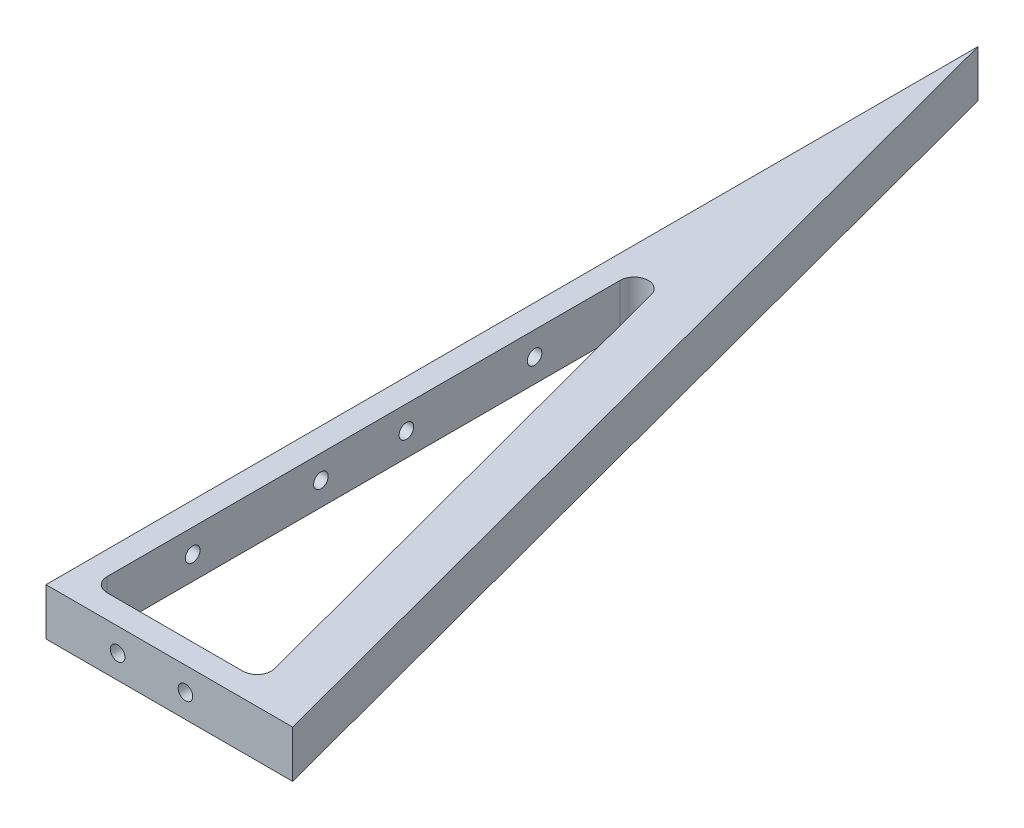
SolidWorks part; units mm, degrees
ref_plane "Front Plane" through (0, 0, 0) normal (0, 0, 1) x (1, 0, 0)
ref_plane "Top Plane" through (0, 0, 0) normal (0, 1, 0) x (1, 0, 0)
ref_plane "Right Plane" through (0, 0, 0) normal (1, 0, 0) x (0, 0, -1)
sketch "Sketch1" plane through (0, 0, 0) normal (0, 1, 0) x (1, 0, 0)
  line L0 (0, 0) -> (0, 198)
  line L1 (0, 198) -> (52.4, 0)
  line L2 (52.4, 0) -> (0, 0)
  line L3 (5, 8) -> (5, 116.9578)
  line L4 (10.9002, 117.7253) -> (39.7354, 8.7675)
  line L5 (36.8353, 5) -> (8, 5)
  arc A0 (5, 116.9578) -> (10.9002, 117.7253) centre (8, 116.9578) cw
  arc A1 (5, 8) -> (8, 5) centre (8, 8) ccw
  arc A2 (39.7354, 8.7675) -> (36.8353, 5) centre (36.8353, 8) cw
  point P6 (40.7325, 5)
  dimension "D6" = 3
  dimension "D1" = 52.4
  dimension "D2" = 5
  dimension "D3" = 5
  dimension "D4" = 10
  dimension "D5" = 198
extrude "Boss-Extrude1" add sketch "Sketch1" along normal blind 10
sketch "Sketch2" plane through (0, 0, -5) normal (0, 0, -1) x (-1, 0, 0)
  line L0 (-36.8353, 5) -> (-8, 5) construction
  line L1 (-36.8353, 10) -> (-36.8353, 0) construction
  line L2 (-8, 10) -> (-8, 0) construction
  line L3 (-22.4176, 10) -> (-22.4176, 0) construction
  line L4 (-8, 10) -> (-36.8353, 10) construction
  line L5 (-8, 0) -> (-36.8353, 0) construction
  circle A0 centre (-15.2076, 5) radius 1.55
  circle A1 centre (-29.6276, 5) radius 1.55
  point P16 (-29.9484, 5)
  point P17 (-15.4904, 5)
  dimension "D4" = 3.1
  dimension "D5" = 3.1
  dimension "D1" = 14.4176
  dimension "D2" = 7.21
  dimension "D3" = 7.21
extrude "Cut-Extrude1" cut sketch "Sketch2" against normal blind 7
sketch "Sketch3" plane through (5, 0, 0) normal (1, 0, 0) x (0, 0, -1)
  line L0 (62.4789, 10) -> (62.4789, 0) construction
  line L1 (116.9578, 10) -> (8, 10) construction
  line L2 (116.9578, 0) -> (8, 0) construction
  line L3 (116.9578, 5) -> (62.4789, 5) construction
  line L4 (116.9578, 10) -> (116.9578, 0) construction
  line L5 (62.4789, 5) -> (8, 5) construction
  line L6 (8, 10) -> (8, 0) construction
  circle A0 centre (98.7978, 5) radius 1.55
  circle A1 centre (71.5578, 5) radius 1.55
  circle A4 centre (53.4, 5) radius 1.55
  circle A5 centre (26.16, 5) radius 1.55
  dimension "D2" = 3.1
  dimension "D3" = 3.1
  dimension "D1" = 54.4789
  dimension "D4" = 18.16
  dimension "D5" = 27.24
extrude "Cut-Extrude2" cut sketch "Sketch3" against normal blind 7
